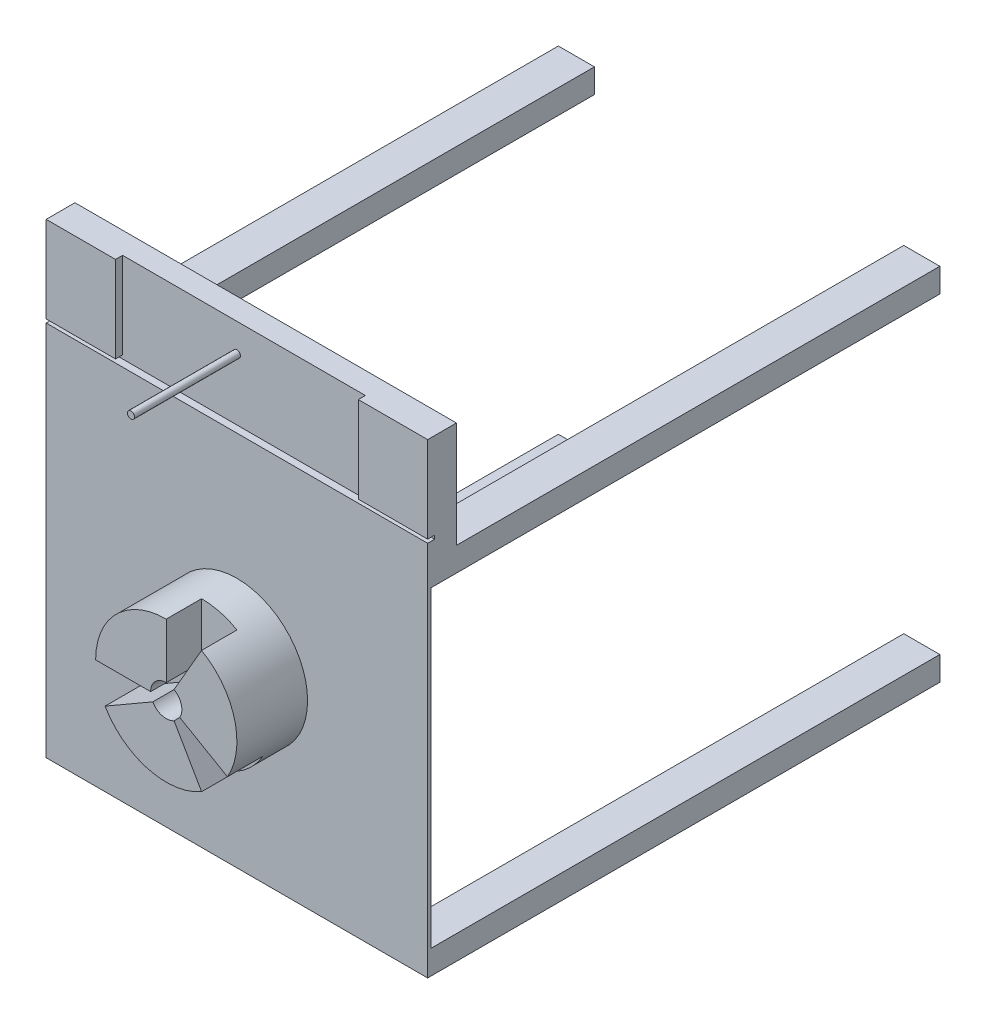
SolidWorks part; units mm, degrees
ref_plane "Front Plane" through (0, 0, 0) normal (0, 0, 1) x (1, 0, 0)
ref_plane "Top Plane" through (0, 0, 0) normal (0, 1, 0) x (1, 0, 0)
ref_plane "Right Plane" through (0, 0, 0) normal (1, 0, 0) x (0, 0, -1)
sketch "Sketch1" plane through (0, 0, 0) normal (0, 0, 1) x (1, 0, 0)
  line L1 (270, -255) -> (-270, -255)
  line L2 (270, -255) -> (270, 255)
  line L3 (270, 255) -> (-270, 255)
  line L4 (-270, -255) -> (-270, 255)
  line L5 (270, -255) -> (-270, 255) construction
  line L6 (270, 255) -> (-270, -255) construction
  point P0 (0, 0)
  dimension "D1" = 540
  dimension "D2" = 510
extrude "Boss-Extrude1" add sketch "Sketch1" along normal blind 5
sketch "Sketch2" plane through (0, 0, 0) normal (0, 0, -1) x (-1, 0, 0)
  line L0 (0, 255) -> (0, 0) construction
  line L1 (-270, 255) -> (270, 255) construction
  line L2 (0, 0) -> (270, 0) construction
  line L3 (270, 255) -> (270, -255) construction
  line L4 (270, 220.9443) -> (218.9402, 220.9443)
  line L5 (-270, 255) -> (-218.9402, 255)
  line L6 (-270, 255) -> (-270, 220.9443)
  line L7 (-270, 220.9443) -> (-218.9402, 220.9443)
  line L8 (-218.9402, 255) -> (-218.9402, 220.9443)
  line L9 (218.9402, 255) -> (218.9402, 220.9443)
  line L10 (270, 255) -> (218.9402, 255)
  line L11 (270, 255) -> (270, 220.9443)
  line L12 (270, -255) -> (270, -220.9443)
  line L13 (270, -255) -> (218.9402, -255)
  line L14 (218.9402, -255) -> (218.9402, -220.9443)
  line L15 (270, -220.9443) -> (218.9402, -220.9443)
  line L16 (-270, -220.9443) -> (-218.9402, -220.9443)
  line L17 (-218.9402, -255) -> (-218.9402, -220.9443)
  line L18 (-270, -255) -> (-218.9402, -255)
  line L19 (-270, -255) -> (-270, -220.9443)
extrude "Boss-Extrude2" add sketch "Sketch2" along normal blind 720
sketch "Sketch3" plane through (0, 0, 5) normal (0, 0, 1) x (1, 0, 0)
  circle A0 centre (0, 0) radius 100
  dimension "D1" = 200
extrude "Boss-Extrude3" add sketch "Sketch3" along normal blind 100
sketch "Sketch4" plane through (0, 255, 0) normal (0, 1, 0) x (1, 0, 0)
  line L0 (270, -5) -> (270, 720) construction
  line L1 (-270, -5) -> (270, -5)
  line L2 (-270, -5) -> (-270, 35.7433)
  line L3 (-270, 35.7433) -> (270, 35.7433)
  line L4 (270, -5) -> (270, 35.7433)
extrude "Boss-Extrude4" add sketch "Sketch4" along normal blind 150
sketch "Sketch5" plane through (0, 0, 5) normal (0, 0, 1) x (1, 0, 0)
  line L0 (0, 0) -> (0, 405) construction
  line L1 (-270, 405) -> (270, 405) construction
  circle A0 centre (0, 375.1918) radius 5
  dimension "D1" = 10
extrude "Boss-Extrude5" add sketch "Sketch5" along normal blind 150
sketch "Sketch6" plane through (0, 0, 5) normal (0, 0, 1) x (1, 0, 0)
  line L0 (-270, 405) -> (270, 405) construction
  line L1 (-171.8161, 405) -> (-171.8161, 282.9375)
  line L2 (-171.8161, 282.9375) -> (-270, 282.9375)
  line L3 (-270, 405) -> (-270, -255) construction
  line L4 (-270, 282.9375) -> (-270, 277.9375)
  line L5 (-270, 277.9375) -> (270, 277.9375)
  line L6 (-171.8161, 405) -> (171.8161, 405)
  line L8 (0, 277.9375) -> (0, 405) construction
  line L9 (270, 282.9375) -> (270, 277.9375)
  line L10 (171.8161, 282.9375) -> (270, 282.9375)
  line L11 (171.8161, 405) -> (171.8161, 282.9375)
  dimension "D1" = 5
extrude "Cut-Extrude1" cut sketch "Sketch6" against normal blind 10
sketch "Sketch7" plane through (0, 0, 105) normal (0, 0, 1) x (1, 0, 0)
  line L0 (0, 100) -> (0, 22.1022)
  line L1 (50, 86.6025) -> (11.0511, 19.1411)
  line L4 (86.6025, -50) -> (19.1411, -11.0511)
  line L5 (50, -86.6025) -> (11.0511, -19.1411)
  line L8 (-86.6025, -50) -> (-19.1411, -11.0511)
  line L9 (-100, 0) -> (-22.1022, 0)
  line L12 (86.6025, 50) -> (0, 0) [skipped]
  line L13 (-50, 86.6025) -> (0, 0) [skipped]
  line L14 (100, 0) -> (0, 0) [skipped]
  line L15 (-86.6025, 50) -> (0, 0) [skipped]
  line L16 (-50, -86.6025) -> (0, 0) [skipped]
  line L17 (0, -100) -> (0, 0) [skipped]
  arc A0 (50, 86.6025) -> (0, 100) centre (0, 0) ccw
  arc A1 (-100, 0) -> (-86.6025, -50) centre (0, 0) ccw
  arc A2 (50, -86.6025) -> (86.6025, -50) centre (0, 0) ccw
  arc A3 (-19.1411, -11.0511) -> (11.0511, -19.1411) centre (0, 0) ccw
  arc A4 (0, 22.1022) -> (-22.1022, 0) centre (0, 0) ccw
  arc A5 (19.1411, -11.0511) -> (11.0511, 19.1411) centre (0, 0) ccw
  point P17 (0, 0)
  dimension "D1" = 12
extrude "Cut-Extrude2" cut sketch "Sketch7" against normal blind 50
